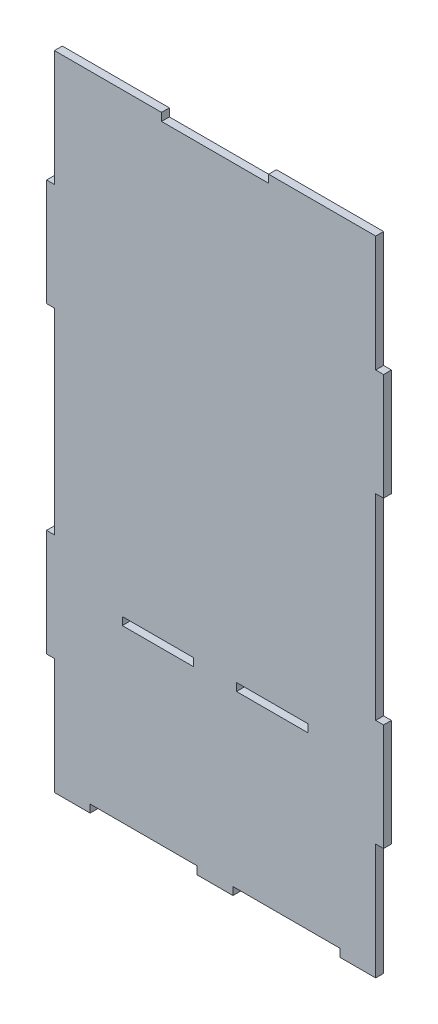
SolidWorks part; units mm, degrees
ref_plane "Front Plane" through (0, 0, 0) normal (0, 0, 1) x (1, 0, 0)
ref_plane "Top Plane" through (0, 0, 0) normal (0, 1, 0) x (1, 0, 0)
ref_plane "Right Plane" through (0, 0, 0) normal (1, 0, 0) x (0, 0, -1)
sketch "Sketch1" plane through (0, 0, 0) normal (0, 0, 1) x (1, 0, 0)
  line L1 (-192.6077, 179.9617) -> (35.9923, 179.9617)
  line L2 (-192.6077, 179.9617) -> (-192.6077, -277.2383)
  line L3 (-192.6077, -277.2383) -> (35.9923, -277.2383)
  line L4 (35.9923, 179.9617) -> (35.9923, -277.2383)
  dimension "D1" = 457.2
  dimension "D2" = 228.6
extrude "Boss-Extrude1" add sketch "Sketch1" along normal blind 5.588
sketch "Sketch2" plane through (0, 0, 5.588) normal (0, 0, 1) x (1, 0, 0)
  line L0 (-192.6077, 179.9617) -> (-192.6077, -277.2383) construction
  line L1 (-198.1957, 97.4117) -> (-192.6077, 97.4117)
  line L2 (-198.1957, 97.4117) -> (-198.1957, 21.2117)
  line L3 (-198.1957, 21.2117) -> (-192.6077, 21.2117)
  line L4 (-192.6077, 97.4117) -> (-192.6077, 21.2117)
  line L6 (-198.1957, -118.4883) -> (-192.6077, -118.4883)
  line L7 (-198.1957, -118.4883) -> (-198.1957, -194.6883)
  line L8 (-198.1957, -194.6883) -> (-192.6077, -194.6883)
  line L9 (-192.6077, -118.4883) -> (-192.6077, -194.6883)
  line L10 (-78.3077, 179.9617) -> (-78.3077, -277.2383) construction
  line L11 (35.9923, 179.9617) -> (-192.6077, 179.9617) construction
  line L12 (-192.6077, -277.2383) -> (35.9923, -277.2383) construction
  line L13 (41.5803, -194.6883) -> (35.9923, -194.6883)
  line L14 (41.5803, -118.4883) -> (41.5803, -194.6883)
  line L15 (35.9923, -118.4883) -> (35.9923, -194.6883)
  line L16 (41.5803, -118.4883) -> (35.9923, -118.4883)
  line L17 (41.5803, 21.2117) -> (35.9923, 21.2117)
  line L18 (41.5803, 97.4117) -> (41.5803, 21.2117)
  line L19 (35.9923, 97.4117) -> (35.9923, 21.2117)
  line L20 (41.5803, 97.4117) -> (35.9923, 97.4117)
  dimension "D1" = 82.55
  dimension "D2" = 76.2
  dimension "D4" = 82.55
  dimension "D5" = 5.588
extrude "Boss-Extrude4" add sketch "Sketch2" against normal through all
sketch "Sketch3" plane through (0, 0, 5.588) normal (0, 0, 1) x (1, 0, 0)
  line L0 (-192.6077, -277.2383) -> (35.9923, -277.2383) construction
  line L1 (-167.2077, -277.2383) -> (-91.0077, -277.2383)
  line L2 (-167.2077, -277.2383) -> (-167.2077, -271.6503)
  line L3 (-167.2077, -271.6503) -> (-91.0077, -271.6503)
  line L4 (-91.0077, -277.2383) -> (-91.0077, -271.6503)
  line L5 (-78.3077, 179.9617) -> (-78.3077, -277.2383) construction
  line L6 (35.9923, 179.9617) -> (-192.6077, 179.9617) construction
  line L7 (-65.6077, -277.2383) -> (-65.6077, -271.6503)
  line L8 (10.5923, -277.2383) -> (10.5923, -271.6503)
  line L9 (10.5923, -277.2383) -> (-65.6077, -277.2383)
  line L10 (10.5923, -271.6503) -> (-65.6077, -271.6503)
  line L11 (35.9923, 97.4117) -> (35.9923, 179.9617) construction
  line L12 (-116.4077, 179.9617) -> (-40.2077, 179.9617)
  line L13 (-116.4077, 179.9617) -> (-116.4077, 174.3737)
  line L14 (-116.4077, 174.3737) -> (-40.2077, 174.3737)
  line L15 (-40.2077, 179.9617) -> (-40.2077, 174.3737)
  dimension "D2" = 76.2
  dimension "D5" = 5.588
  dimension "D3" = 5.588
  dimension "D1" = 25.4
  dimension "D4" = 76.2
  dimension "D6" = 76.2
extrude "Cut-Extrude1" cut sketch "Sketch3" against normal blind 5.588
sketch "Sketch4" plane through (0, 0, 0) normal (0, 0, 1) x (1, 0, 0)
  line L3 (-144.3477, -144.6503) -> (-93.5477, -144.6503)
  line L4 (-144.3477, -144.6503) -> (-144.3477, -150.2383)
  line L5 (-144.3477, -150.2383) -> (-93.5477, -150.2383)
  line L6 (-93.5477, -144.6503) -> (-93.5477, -150.2383)
  line L7 (-78.3077, 174.3737) -> (-78.3077, -278.1638) construction
  line L8 (-116.4077, 174.3737) -> (-40.2077, 174.3737) construction
  line L9 (-63.0677, -144.6503) -> (-63.0677, -150.2383)
  line L10 (-12.2677, -150.2383) -> (-63.0677, -150.2383)
  line L11 (-12.2677, -144.6503) -> (-12.2677, -150.2383)
  line L12 (-12.2677, -144.6503) -> (-63.0677, -144.6503)
  line L14 (-91.0077, -277.2383) -> (-65.6077, -277.2383) construction
  dimension "D1" = 50.8
  dimension "D2" = 5.588
  dimension "D3" = 15.24
  dimension "D4" = 127
extrude "Cut-Extrude5" cut sketch "Sketch4" against normal through all and the other way through all
equation "\"width\"= 9in"
equation "\"Height\"= 18in"
equation "\"thick\"= 0.22"
equation "\"D1@Sketch1\"=\"Height\""
equation "\"D2@Sketch1\"=\"width\""
equation "\"D1@Boss-Extrude1\"=\"thick\""
equation "\"D5@Sketch2\"=\"thick\""
equation "\"D1\"= \"thick\""
equation "\"D3@Sketch3\"=\"thick\""
equation "\"D1@Cut-Extrude1\"=\"thick\""
equation "\"D5@Sketch3\"=\"thick\""
equation "\"D2@Sketch4\"=\"thick\""
